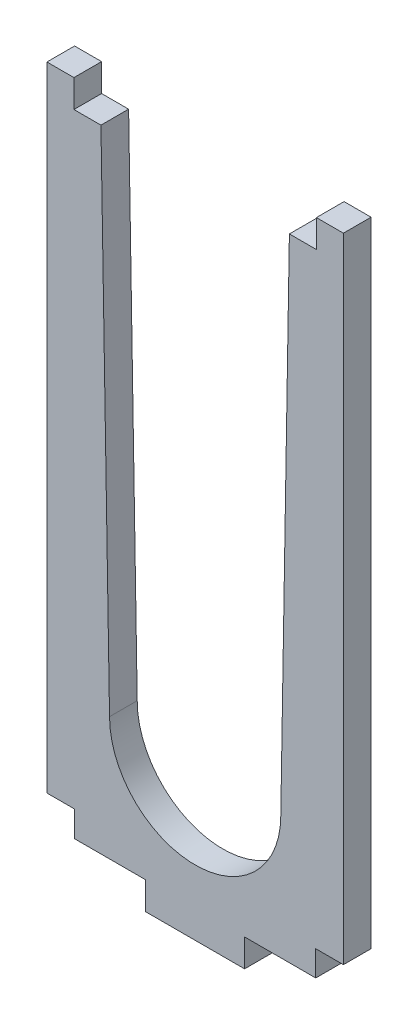
SolidWorks part; units mm, degrees
ref_plane "Front Plane" through (0, 0, 0) normal (0, 0, 1) x (1, 0, 0)
ref_plane "Top Plane" through (0, 0, 0) normal (0, 1, 0) x (1, 0, 0)
ref_plane "Right Plane" through (0, 0, 0) normal (1, 0, 0) x (0, 0, -1)
sketch "Sketch8" plane through (0, 0, 0) normal (0, 0, 1) x (1, 0, 0)
  line L1 (0, 0) -> (57.15, 0)
  line L2 (0, 0) -> (0, 127)
  line L3 (0, 127) -> (57.15, 127)
  line L4 (57.15, 0) -> (57.15, 127)
  dimension "D1" = 57.15
  dimension "D2" = 127
extrude "Boss-Extrude3" add sketch "Sketch8" along normal blind 5.334
sketch "Sketch9" plane through (0, 0, 5.334) normal (0, 0, 1) x (1, 0, 0)
  line L0 (0, 127) -> (10.414, 127)
  line L1 (57.15, 127) -> (0, 127) construction
  line L2 (28.575, 0) -> (28.575, 12.573) construction
  line L3 (57.15, 127) -> (46.736, 127)
  line L4 (57.15, 127) -> (46.736, 127)
  line L5 (0, 0) -> (57.15, 0) construction
  line L6 (28.575, 29.083) -> (28.575, 12.573) construction
  line L7 (10.414, 127) -> (12.0698, 29.083)
  line L8 (46.736, 127) -> (45.0802, 29.083)
  circle A0 centre (28.575, 29.083) radius 16.5052
  line M9 (57.15, 127) -> (0, 127)
  dimension "D1" = 10.414
  dimension "D2" = 10.414
  dimension "D3" = 12.573
  dimension "D4" = 16.51
extrude "Cut-Extrude4" cut sketch "Sketch9" against normal through all contours A0 L8 L7 M9 | A0
sketch "Sketch12" plane through (0, 0, 0) normal (0, -1, 0) x (-1, 0, 0)
  line L0 (0, -5.334) -> (-57.15, -5.334) construction
  line L1 (-57.15, 0) -> (-38.1, 0)
  line L2 (-57.15, 0) -> (-57.15, -5.334)
  line L3 (-57.15, -5.334) -> (-38.1, -5.334)
  line L4 (-38.1, 0) -> (-38.1, -5.334)
  line L5 (-38.1, -5.334) -> (-19.05, -5.334) construction
  line L6 (0, 0) -> (-19.05, 0)
  line L7 (0, 0) -> (0, -5.334)
  line L8 (0, -5.334) -> (-19.05, -5.334)
  line L9 (-19.05, 0) -> (-19.05, -5.334)
extrude "Cut-Extrude8" cut sketch "Sketch12" against normal blind 5.334
sketch "Sketch14" plane through (0, 127, 0) normal (0, 1, 0) x (1, 0, 0)
  line L1 (46.736, 0) -> (57.15, 0)
  line L2 (46.736, 0) -> (46.736, -5.334)
  line L3 (46.736, -5.334) -> (57.15, -5.334)
  line L4 (57.15, 0) -> (57.15, -5.334)
  line L5 (0, 0) -> (10.414, 0)
  line L6 (0, 0) -> (0, -5.334)
  line L7 (0, -5.334) -> (10.414, -5.334)
  line L8 (10.414, 0) -> (10.414, -5.334)
extrude "Boss-Extrude4" add sketch "Sketch14" along normal blind 5.334
sketch "Sketch15" plane through (0, 132.334, 0) normal (0, 1, 0) x (1, 0, 0)
  line L0 (0, -5.334) -> (10.414, -5.334) construction
  line L1 (10.414, 0) -> (5.207, 0)
  line L2 (10.414, 0) -> (10.414, -5.334)
  line L3 (10.414, -5.334) -> (5.207, -5.334)
  line L4 (5.207, 0) -> (5.207, -5.334)
  line L5 (5.207, 0) -> (0, 0) construction
  line L6 (46.736, -5.334) -> (57.15, -5.334) construction
  line L7 (46.736, 0) -> (51.943, 0)
  line L8 (46.736, 0) -> (46.736, -5.334)
  line L9 (46.736, -5.334) -> (51.943, -5.334)
  line L10 (51.943, 0) -> (51.943, -5.334)
  line L11 (51.943, 0) -> (57.15, 0) construction
extrude "Cut-Extrude9" cut sketch "Sketch15" against normal blind 5.334
sketch "Sketch16" plane through (0, 0, 0) normal (-1, 0, 0) x (0, 0, 1)
  line L0 (5.334, 132.334) -> (5.334, 5.334) construction
  line L1 (0, 5.334) -> (5.334, 5.334)
  line L2 (0, 5.334) -> (0, 9.8425)
  line L3 (0, 9.8425) -> (5.334, 9.8425)
  line L4 (5.334, 5.334) -> (5.334, 9.8425)
  line L5 (0, 9.8425) -> (4.7625, 9.8425) construction
extrude "Cut-Extrude10" cut sketch "Sketch16" against normal blind 5.334
sketch "Sketch19" plane through (57.15, 0, 0) normal (1, 0, 0) x (0, 0, -1)
  line L0 (-4.7625, 9.8425) -> (0, 9.8425) construction
  line L1 (0, 5.334) -> (-4.7625, 5.334)
  line L2 (0, 5.334) -> (0, 9.8425)
  line L3 (0, 9.8425) -> (-4.7625, 9.8425)
  line L4 (-4.7625, 5.334) -> (-4.7625, 9.8425)
extrude "Cut-Extrude12" cut sketch "Sketch19" against normal blind 5.334
sketch "Sketch20" plane through (0, 0, 4.7625) normal (0, 0, -1) x (-1, 0, 0)
  line L1 (-57.15, 9.8425) -> (-51.816, 9.8425)
  line L2 (-57.15, 9.8425) -> (-57.15, 5.334)
  line L3 (-57.15, 5.334) -> (-51.816, 5.334)
  line L4 (-51.816, 9.8425) -> (-51.816, 5.334)
extrude "Cut-Extrude13" cut sketch "Sketch20" against normal through all
sketch "Sketch21" plane through (0, 0, 5.334) normal (0, 0, 1) x (1, 0, 0)
  line L0 (57.15, 9.8425) -> (57.15, 132.334) construction
  line L1 (0, 9.8425) -> (5.3358, 9.8425)
  line L2 (0, 9.8425) -> (0, 10.2997)
  line L3 (0, 10.2997) -> (5.3358, 10.2997)
  line L4 (5.3358, 9.8425) -> (5.3358, 10.2997)
  line L5 (51.816, 9.8425) -> (57.15, 9.8425)
  line L6 (51.816, 9.8425) -> (51.816, 10.2235)
  line L7 (51.816, 10.2235) -> (57.15, 10.2235)
  line L8 (57.15, 9.8425) -> (57.15, 10.2235)
  dimension "D1" = 0.4572
extrude "Cut-Extrude14" cut sketch "Sketch21" against normal through all
equation "\"Foamcore\"= .1875in"
equation "\"Mdf\"= .21in"
equation "\"Gmaterial\"= \"Mdf\""
equation "\"D1@Boss-Extrude3\"= \"Gmaterial\""
equation "\"D1@Cut-Extrude9\"=\"Gmaterial\""
equation "\"D1@Cut-Extrude8\"=\"Gmaterial\""
equation "\"D1@Cut-Extrude10\"=\"Gmaterial\""
equation "\"D1@Cut-Extrude12\"=\"Gmaterial\""
equation "\"D1@Boss-Extrude4\"= \"Gmaterial\""
equation "\"D2@Sketch9\"=0.41in"
equation "\"D1@Sketch9\"=0.41in"
equation "\"D1@Sketch21\"=.018"
equation "\"D2@Sketch8\"=5in"
equation "\"D3@Sketch9\"=0.495in"
